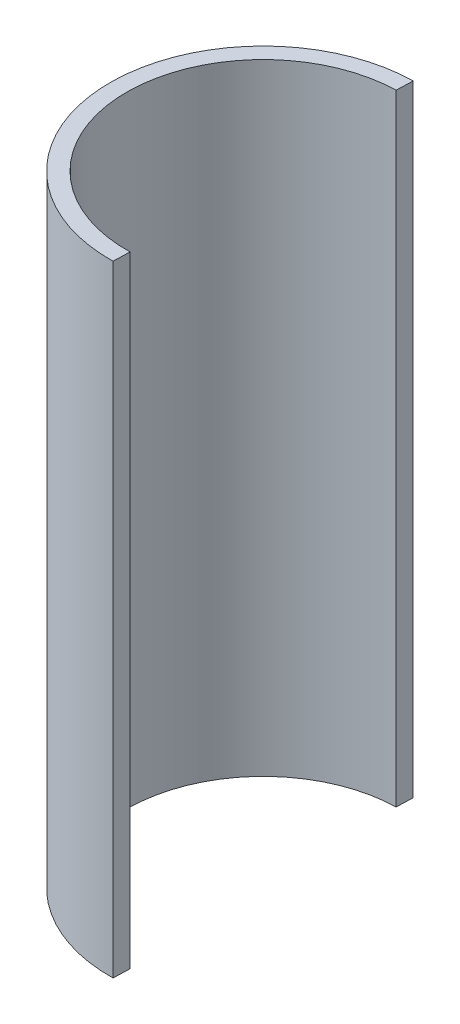
SolidWorks part; units mm, degrees
ref_plane "Front Plane" through (0, 0, 0) normal (0, 0, 1) x (1, 0, 0)
ref_plane "Top Plane" through (0, 0, 0) normal (0, 1, 0) x (1, 0, 0)
ref_plane "Right Plane" through (0, 0, 0) normal (1, 0, 0) x (0, 0, -1)
sketch "Sketch1" plane through (0, 0, 0) normal (0, 1, 0) x (1, 0, 0)
  line L0 (-0.7254, 36.9929) -> (-0.8553, 32.9889)
  line L1 (0.8553, -32.9889) -> (0.7254, -36.9929)
  arc A0 (-0.8553, 32.9889) -> (0.8553, -32.9889) centre (0, 0) ccw
  arc A1 (-0.7254, 36.9929) -> (0.7254, -36.9929) centre (0, 0) ccw
  dimension "D1" = 33
  dimension "D2" = 37
extrude "Boss-Extrude1" add sketch "Sketch1" along normal blind 150
